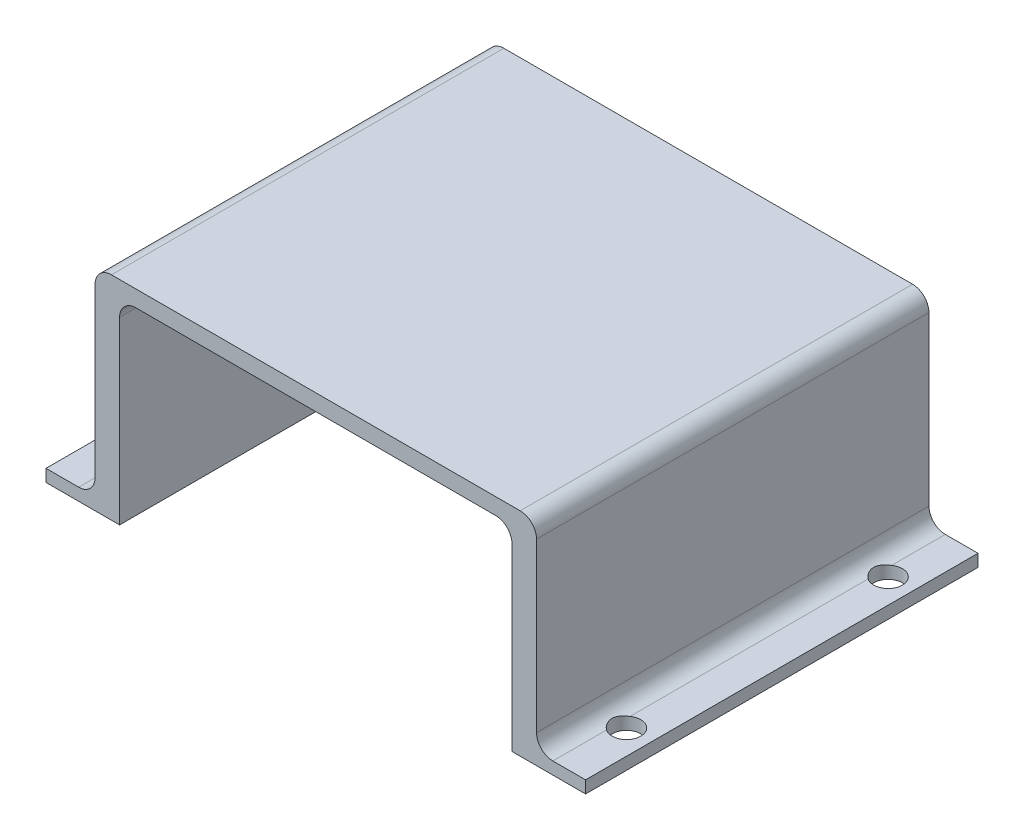
SolidWorks part; units mm, degrees
material "ABS"
ref_plane "Front Plane" through (0, 0, 0) normal (0, 0, 1) x (1, 0, 0)
ref_plane "Top Plane" through (0, 0, 0) normal (0, 1, 0) x (1, 0, 0)
ref_plane "Right Plane" through (0, 0, 0) normal (1, 0, 0) x (0, 0, -1)
sketch "Sketch1" plane through (0, 0, 0) normal (0, 0, 1) x (1, 0, 0)
  line L0 (0, 0) -> (14.2875, 0)
  line L1 (14.2875, 0) -> (14.2875, 38.1)
  line L2 (14.2875, 38.1) -> (90.4875, 38.1)
  line L3 (90.4875, 38.1) -> (90.4875, 0)
  line L4 (90.4875, 0) -> (104.775, 0)
  line L5 (104.775, 0) -> (104.775, 2.3812)
  line L6 (104.775, 2.3812) -> (95.25, 2.3812)
  line L7 (95.25, 2.3812) -> (95.25, 41.275)
  line L8 (95.25, 41.275) -> (9.525, 41.275)
  line L9 (9.525, 41.275) -> (9.525, 2.3812)
  line L10 (0, 0) -> (0, 2.3812)
  line L11 (0, 2.3812) -> (9.525, 2.3812)
  dimension "D1" = 9.525
  dimension "D2" = 14.2875
  dimension "D3" = 3.175
  dimension "D4" = 76.2
  dimension "D5" = 38.1
  dimension "D6" = 2.3813
extrude "Boss-Extrude1" add sketch "Sketch1" along normal blind 76.2
fillet "Fillet1" radius 3.175 6 edges at (90.4875, 38.1, 38.1) (14.2875, 38.1, 38.1) (95.25, 2.3812, 38.1) (95.25, 41.275, 38.1) (9.525, 2.3812, 38.1) (9.525, 41.275, 38.1)
sketch "Sketch4" plane through (0, 2.3812, 0) normal (0, 1, 0) x (1, 0, 0)
  line L0 (104.775, 0) -> (98.425, 0) construction
  line L1 (104.775, -76.2) -> (98.425, -76.2) construction
  line L3 (104.775, -76.2) -> (104.775, 0) construction
  line L4 (0, -76.2) -> (0, 0) construction
  circle A0 centre (100.0125, -12.7) radius 2.7781
  circle A1 centre (100.0125, -63.5) radius 2.7781
  circle A2 centre (4.7625, -63.5) radius 2.7781
  circle A3 centre (4.7625, -12.7) radius 2.7781
  dimension "D1" = 12.7
  dimension "D2" = 5.5562
  dimension "D3" = 12.7
  dimension "D4" = 4.7625
  dimension "D5" = 4.7625
extrude "Cut-Extrude1" cut sketch "Sketch4" against normal mid plane 12.7
equation "\"D2@Sketch1\"=\"D1@Sketch1\"+3/16"
